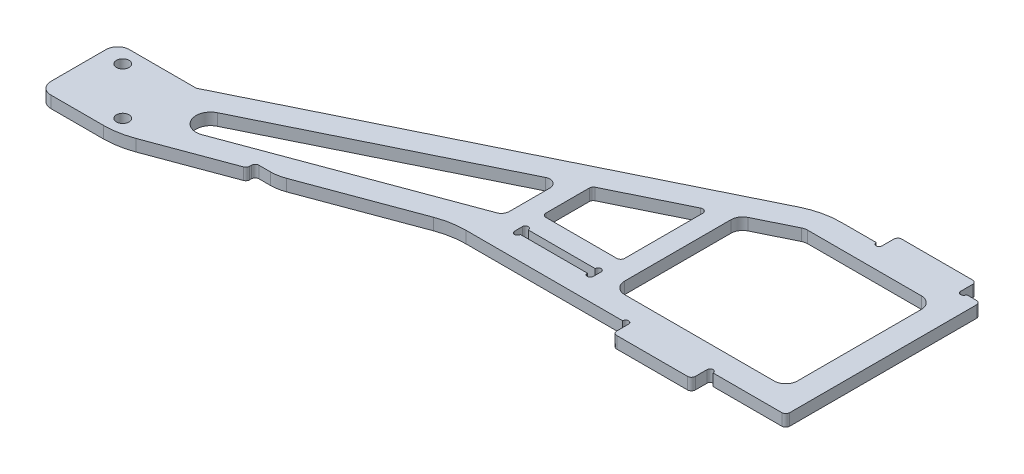
SolidWorks part; units mm, degrees
material "Thornel Mat VMA"
ref_plane "前视基准面" through (0, 0, 0) normal (0, 0, 1) x (1, 0, 0)
ref_plane "上视基准面" through (0, 0, 0) normal (0, 1, 0) x (1, 0, 0)
ref_plane "右视基准面" through (0, 0, 0) normal (1, 0, 0) x (0, 0, -1)
sketch "草图1" plane through (0, 0, 0) normal (0, 1, 0) x (1, 0, 0)
  line L0 (0, 0) -> (20, 0)
  line L1 (20, 0) -> (20, 49.5)
  line L2 (20, 49.5) -> (15, 49.5)
  line L3 (15, 49.5) -> (15, 53.5)
  line L4 (15, 53.5) -> (-5, 53.5)
  line L5 (-5, 53.5) -> (-5, 49.5)
  line L6 (-5, 49.5) -> (-20, 49.5)
  line L7 (-20, 49.5) -> (-127, -3)
  line L8 (-127, -3) -> (-147, -3)
  line L9 (-147, -3) -> (-147, -23)
  line L10 (-147, -23) -> (-127, -23)
  line L11 (-127, -23) -> (-103, -14.0968)
  line L12 (-65, 0) -> (-20, 0)
  line L13 (-20, 0) -> (-20, -4)
  line L14 (-20, -4) -> (0, -4)
  line L15 (0, -4) -> (0, 0)
  line L16 (-55, 8) -> (-35, 8)
  line L17 (-55, 8) -> (-55, 6)
  line L18 (-35, 8) -> (-35, 6)
  line L19 (-55, 6) -> (-35, 6)
  line L20 (-97.3478, -12) -> (-103, -12)
  line L21 (-103, -12) -> (-103, -14.0968)
  line L22 (-97.3478, -12) -> (-65, 0)
  circle A0 centre (-141.7, -7) radius 1.6
  circle A1 centre (-129.7, -19) radius 1.6
  dimension "D17" = 3.2
  dimension "D18" = 5.3
  dimension "D21" = 12
  dimension "D22" = 44
  dimension "D23" = 11
  dimension "D1" = 4
  dimension "D2" = 4
  dimension "D3" = 20
  dimension "D4" = 20
  dimension "D5" = 49.5
  dimension "D6" = 20
  dimension "D7" = 167
  dimension "D8" = 23
  dimension "D9" = 20
  dimension "D10" = 20
  dimension "D11" = 45
  dimension "D12" = 15
  dimension "D13" = 2
  dimension "D14" = 6
  dimension "D15" = 20
  dimension "D16" = 55
  dimension "D19" = 4
  dimension "D20" = 4
  dimension "D25" = 5
  dimension "D26" = 20
extrude "凸台-拉伸1" add sketch "草图1" along normal blind 3
sketch "草图2" plane through (0, 3, 0) normal (0, 1, 0) x (1, 0, 0)
  line L0 (-35, 6) -> (-35, 8) construction
  line L1 (14, 6) -> (-30, 6)
  line L2 (14, 6) -> (14, 43.5)
  line L3 (14, 43.5) -> (-18.6073, 43.5)
  line L4 (-30, 6) -> (-30, 37.9101)
  line L5 (-35, 35.4569) -> (-35, 13)
  line L6 (-35, 13) -> (-55, 13)
  line L7 (-55, 13) -> (-55, 25.6438)
  line L8 (-30, 37.9101) -> (-18.6073, 43.5)
  line L9 (-127, -3) -> (-127, -23) construction
  line L10 (-121, -9.0485) -> (-127, -9.0485) construction
  line L12 (-20, 49.5) -> (-127, -3) construction
  line L18 (-60, 9.6456) -> (-60, 19.9814)
  line L19 (-55, 8) -> (-55, 6) construction
  line L20 (-5, 49.5) -> (-20, 49.5) construction
  line L21 (20, 0) -> (20, 49.5) construction
  line L22 (-65, 0) -> (-20, 0) construction
  line L25 (-55, 25.6438) -> (-35, 35.4569)
  line L29 (-129.0868, -17.3746) -> (-105.0868, -8.4714)
  line L30 (-116.0064, -12.5222) -> (-61.3044, 7.7705)
  line L31 (20, 49.5) -> (15, 49.5) construction
  line L34 (0, 0) -> (20, 0) construction
  line L35 (-35, 8) -> (-55, 8) construction
  line L36 (-55, 6) -> (-35, 6) construction
  line L39 (-62.881, 21.777) -> (-118.927, -5.7223)
  arc A0 (-116.0064, -12.5222) -> (-118.927, -5.7223) centre (-117.295, -9.0485) cw
  arc A1 (-61.3044, 7.7705) -> (-60, 9.6456) centre (-62, 9.6456) ccw
  arc A2 (-60, 19.9814) -> (-62.881, 21.777) centre (-62, 19.9814) ccw
  circle A3 centre (-5.75, 49.5) radius 0.75
  circle A4 centre (15.75, 49.5) radius 0.75
  circle A5 centre (0.75, 0) radius 0.75
  circle A6 centre (-20.75, 0) radius 0.75
  circle A7 centre (-54.25, 8) radius 0.75
  circle A8 centre (-54.25, 6) radius 0.75
  circle A9 centre (-35.75, 6) radius 0.75
  circle A10 centre (-35.75, 8) radius 0.75
  dimension "D3" = 6
  dimension "D4" = 2
  dimension "D5" = 2
  dimension "D10" = 1.5
  dimension "D11" = 5
  dimension "D2" = 5
  dimension "D6" = 6
  dimension "D7" = 6
  dimension "D8" = 6
  dimension "D9" = 5
  dimension "D12" = 6
  dimension "D13" = 6
extrude "切除-拉伸1" cut sketch "草图2" against normal through all
fillet "圆角1" radius 3 7 edges at (14, 1.5, -43.5) (14, 1.5, -6) (-30, 1.5, -6) (-147, 1.5, 3) (-147, 1.5, 23) (-18.6073, 1.5, -43.5) (-30, 1.5, -37.9101)
fillet "圆角2" radius 20 3 edges at (-127, 1.5, 23) (-20, 1.5, -49.5) (-65, 1.5, 0)
fillet "圆角3" radius 1 12 edges at (-20, 1.5, 4) (0, 1.5, 4) (20, 1.5, 0) (20, 1.5, -49.5) (15, 1.5, -53.5) (-5, 1.5, -53.5) (-35, 1.5, -35.4569) (-35, 1.5, -13) (-55, 1.5, -13) (-55, 1.5, -25.6438) (-103, 1.5, 12) (-103, 1.5, 14.0968)
fillet "圆角4" radius 10 1 edges at (-97.3478, 1.5, 12)
